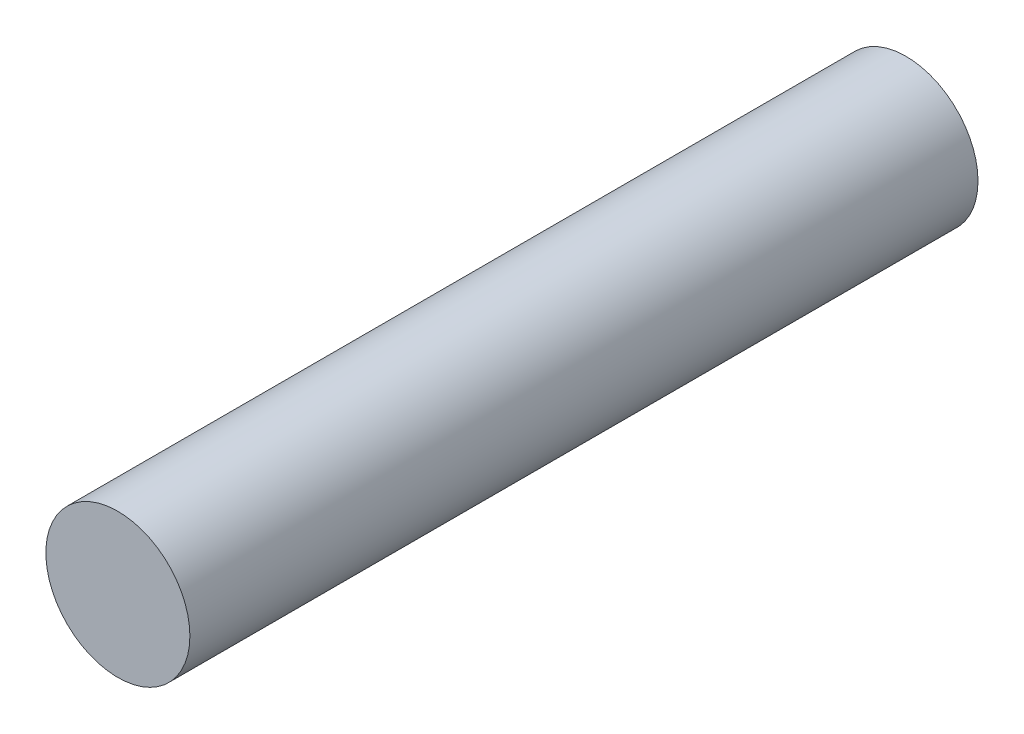
SolidWorks part; units mm, degrees
ref_plane "前视基准面" through (0, 0, 0) normal (0, 0, 1) x (1, 0, 0)
ref_plane "上视基准面" through (0, 0, 0) normal (0, 1, 0) x (1, 0, 0)
ref_plane "右视基准面" through (0, 0, 0) normal (1, 0, 0) x (0, 0, -1)
sketch "草图1" plane through (0, 0, 0) normal (0, 0, 1) x (1, 0, 0)
  circle A0 centre (0, 0) radius 53
  dimension "D1" = 106
extrude "凸台-拉伸1" add sketch "草图1" along normal blind 580
